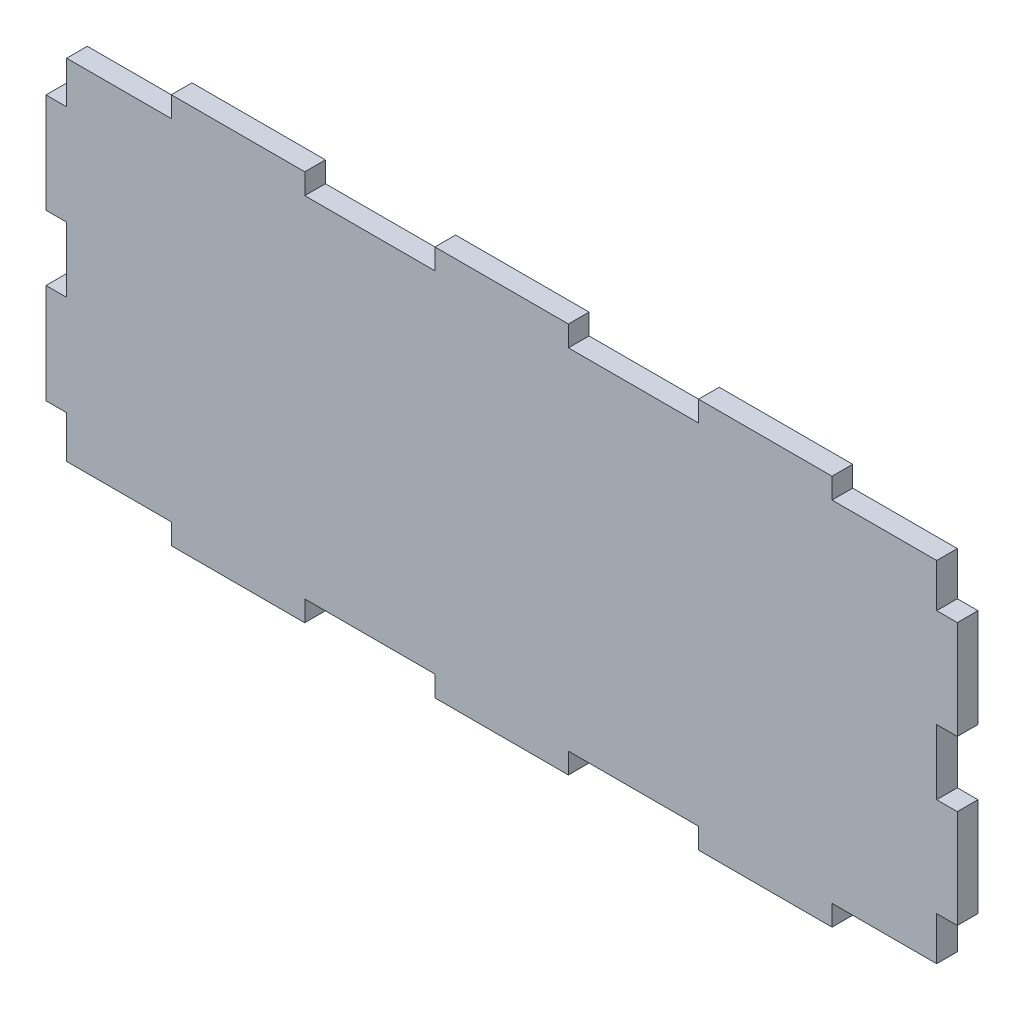
SolidWorks part; units mm, degrees
ref_plane "Front Plane" through (0, 0, 0) normal (0, 0, 1) x (1, 0, 0)
ref_plane "Top Plane" through (0, 0, 0) normal (0, 1, 0) x (1, 0, 0)
ref_plane "Right Plane" through (0, 0, 0) normal (1, 0, 0) x (0, 0, -1)
sketch "Sketch1" plane through (0, 0, 0) normal (0, 0, 1) x (1, 0, 0)
  line L1 (-64.0181, -3.175) -> (75.9819, -3.175)
  line L2 (-64.0181, -3.175) -> (-64.0181, 56.825)
  line L3 (-64.0181, 56.825) -> (75.9819, 56.825)
  line L4 (75.9819, -3.175) -> (75.9819, 56.825)
extrude "Boss-Extrude1" add sketch "Sketch1" against normal up to surface (3.175 mm away)
sketch "Sketch2" plane through (0, 0, 0) normal (0, 0, 1) x (1, 0, 0)
  line L0 (-60.8431, 0) -> (-44.7681, 0)
  line L1 (56.7319, 0) -> (72.8069, 0)
  line L2 (75.9819, -3.175) -> (75.9819, 56.825) construction
  line L3 (-64.0181, -3.175) -> (75.9819, -3.175) construction
  line L4 (75.9819, 26.825) -> (-64.0181, 26.825) construction
  line L5 (75.9819, 46.975) -> (75.9819, 53.65)
  line L6 (72.8069, 46.975) -> (75.9819, 46.975)
  line L7 (72.8069, 53.65) -> (72.8069, 46.975)
  line L8 (75.9819, 53.65) -> (75.9819, 56.825)
  line L9 (56.7319, 56.825) -> (56.7319, 53.65)
  line L10 (75.9819, 56.825) -> (56.7319, 56.825)
  line L11 (36.2319, 53.65) -> (36.2319, 56.825)
  line L12 (16.2319, 53.65) -> (36.2319, 53.65)
  line L13 (16.2319, 56.825) -> (16.2319, 53.65)
  line L14 (36.2319, 56.825) -> (16.2319, 56.825)
  line L15 (-24.2681, 56.825) -> (-24.2681, 53.65)
  line L16 (-4.2681, 56.825) -> (-24.2681, 56.825)
  line L17 (-4.2681, 53.65) -> (-4.2681, 56.825)
  line L18 (-24.2681, 53.65) -> (-4.2681, 53.65)
  line L19 (-64.0181, 56.825) -> (-64.0181, 53.65)
  line L20 (-44.7681, 56.825) -> (-64.0181, 56.825)
  line L21 (-44.7681, 53.65) -> (-44.7681, 56.825)
  line L22 (-60.8431, 47.175) -> (-60.8431, 53.65)
  line L23 (-64.0181, 47.175) -> (-60.8431, 47.175)
  line L24 (-64.0181, 53.65) -> (-64.0181, 47.175)
  line L25 (56.7319, 53.65) -> (72.8069, 53.65)
  line L26 (-60.8431, 53.65) -> (-44.7681, 53.65)
  line L27 (5.9819, 56.825) -> (5.9819, -3.175) construction
  line L28 (75.9819, 56.825) -> (-64.0181, 56.825) construction
  line L29 (75.9819, 21.825) -> (75.9819, 31.825)
  line L30 (72.8069, 21.825) -> (75.9819, 21.825)
  line L31 (72.8069, 31.825) -> (72.8069, 21.825)
  line L32 (75.9819, 31.825) -> (72.8069, 31.825)
  line L44 (-64.0181, 31.825) -> (-60.8431, 31.825)
  line L45 (-60.8431, 31.825) -> (-60.8431, 21.825)
  line L46 (-60.8431, 21.825) -> (-64.0181, 21.825)
  line L47 (-64.0181, 21.825) -> (-64.0181, 31.825)
  line L49 (-64.0181, 0) -> (-64.0181, 6.475)
  line L50 (-64.0181, 6.475) -> (-60.8431, 6.475)
  line L51 (-60.8431, 6.475) -> (-60.8431, 0)
  line L53 (-44.7681, 0) -> (-44.7681, -3.175)
  line L54 (-44.7681, -3.175) -> (-64.0181, -3.175)
  line L55 (-64.0181, -3.175) -> (-64.0181, 0)
  line L56 (-24.2681, 0) -> (-4.2681, 0)
  line L57 (-4.2681, 0) -> (-4.2681, -3.175)
  line L58 (-4.2681, -3.175) -> (-24.2681, -3.175)
  line L59 (-24.2681, -3.175) -> (-24.2681, 0)
  line L60 (36.2319, -3.175) -> (16.2319, -3.175)
  line L61 (16.2319, -3.175) -> (16.2319, 0)
  line L62 (16.2319, 0) -> (36.2319, 0)
  line L63 (36.2319, 0) -> (36.2319, -3.175)
  line L64 (75.9819, -3.175) -> (56.7319, -3.175)
  line L65 (56.7319, -3.175) -> (56.7319, 0)
  line L67 (75.9819, 0) -> (75.9819, -3.175)
  line L69 (72.8069, 0) -> (72.8069, 6.675)
  line L70 (72.8069, 6.675) -> (75.9819, 6.675)
  line L71 (75.9819, 6.675) -> (75.9819, 0)
  dimension "D1" = 19.25
  dimension "D2" = 20.5
  dimension "D3" = 20
  dimension "D4" = 20.5
  dimension "D5" = 20
  dimension "D6" = 20.5
  dimension "D7" = 0
  dimension "D8" = 3.175
  dimension "D9" = 3.175
  dimension "D10" = 3.175
  dimension "D11" = 9.65
  dimension "D12" = 0
  dimension "D13" = 25
  dimension "D14" = 10
extrude "Cut-Extrude1" cut sketch "Sketch2" against normal up to surface (3.175 mm away) up to face at (5.9819, 26.825, -3.175)
